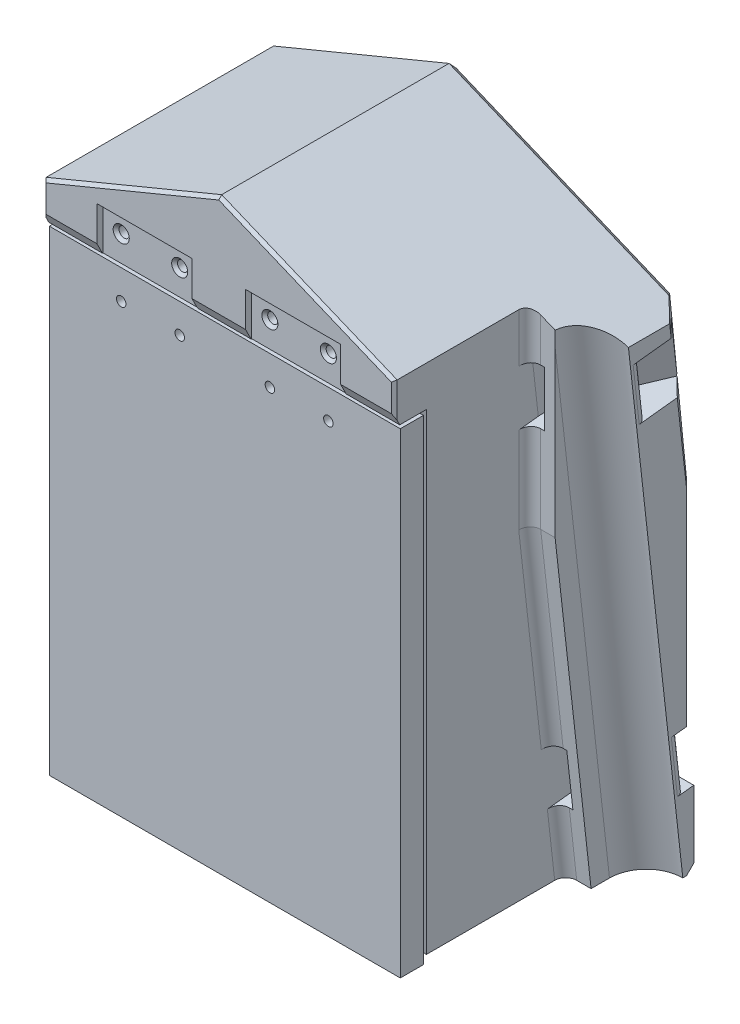
SolidWorks part; units mm, degrees
other "House"
other "Door"
other "Cover" parameters "D1"=134.3446, "D2"=7.568, "D3"=4.0473, "D4"=11.5
ref_plane "Front Plane" through (0, 0, 0) normal (0, 0, 1) x (1, 0, 0)
ref_plane "Top Plane" through (0, 0, 0) normal (0, 1, 0) x (1, 0, 0)
ref_plane "Right Plane" through (0, 0, 0) normal (1, 0, 0) x (0, 0, -1)
sketch "Sketch1" plane through (0, 0, 0) normal (0, 0, 1) x (1, 0, 0)
  line L0 (-48, 73.5589) -> (-48, -66.5589)
  line L1 (-45, -61.5589) -> (45, -61.5589)
  line L2 (-45, -61.5589) -> (-45, 61.5589)
  line L3 (-45, 61.5589) -> (45, 61.5589)
  line L4 (45, -61.5589) -> (45, 61.5589)
  line L5 (0, 61.5589) -> (0, -61.5589) construction
  line L6 (-45, 0) -> (45, 0) construction
  line L7 (-48, -66.5589) -> (48, -66.5589)
  line L8 (48, -66.5589) -> (48, 73.5589)
  line L9 (48, 73.5589) -> (0, 93.4411)
  line L10 (0, 93.4411) -> (-48, 73.5589)
  point P0 (0, 0)
  dimension "D1" = 160
  dimension "D2" = 90
  dimension "D3" = 22.5
  dimension "D4" = 12
  dimension "D5" = 5
  dimension "D6" = 3
  dimension "D7" = 123.1177
extrude "main-extrude" add sketch "Sketch1" along normal blind 60
sketch "Sketch2" plane through (0, 0, 0) normal (0, 0, 1) x (1, 0, 0)
  line L0 (48, -66.5589) -> (48, 73.5589) construction
  line L1 (-48, -66.5589) -> (48, -66.5589) construction
  line L2 (-48, 73.5589) -> (-48, -66.5589) construction
  line L3 (48, 73.5589) -> (0, 93.4411) construction
  line L4 (0, 93.4411) -> (-48, 73.5589) construction
  line L5 (48, -66.5589) -> (48, 73.5589)
  line L6 (-48, -66.5589) -> (48, -66.5589)
  line L7 (-48, 73.5589) -> (-48, -66.5589)
  line L8 (48, 73.5589) -> (0, 93.4411)
  line L9 (0, 93.4411) -> (-48, 73.5589)
extrude "rear-extrude" add sketch "Sketch2" against normal blind 5
sketch "Sketch6" plane through (0, -66.5589, 0) normal (0, -1, 0) x (1, 0, 0)
  line L0 (48, 22.9375) -> (53, 22.9375)
  line L1 (64.9375, 15) -> (64.9375, 22.9375)
  line L2 (53, 22.9375) -> (57, 22.9375)
  line L3 (-48, -5) -> (48, -5) construction
  line L4 (64.9375, 15) -> (64.9375, -5)
  line L5 (64.9375, -5) -> (48, -5)
  line L6 (48, 60) -> (48, -5) construction
  line L7 (48, -5) -> (48, 22.9375)
  line L8 (64.9375, 22.9375) -> (57, 22.9375)
  circle A0 centre (64.9375, 22.9375) radius 7.9375 construction
  arc A1 (64.9375, 15) -> (57, 22.9375) centre (64.9375, 22.9375) cw construction
  point P3 (64.9375, 15)
  dimension "D3" = 15.875
  dimension "D1" = 5
  dimension "D2" = 4
  dimension "D4" = 20
extrude "Boss-Extrude3" add sketch "Sketch6" against normal up to surface (140.1177 mm away)
sketch "Sketch19" plane through (64.9375, 0, 0) normal (1, 0, 0) x (0, 0, -1)
  line L0 (-7.4036, -72.4527) -> (-21.3291, 52.151) construction
  line L2 (-22.9375, 66.5431) -> (-32.8756, 65.4325) construction
  line L3 (-7.9381, -67.6695) -> (2, -66.5589) construction
  line L6 (5, -66.5589) -> (-22.9375, -66.5589) construction
  dimension "D1" = 10
  dimension "D3" = 3
ref_plane "Plane6" through (64.9375, -67.6695, 7.9381) normal (0, 0.9938, 0.1111) x (1, 0, 0)
sketch "Sketch20" plane through (64.9375, -67.6695, 7.9381) normal (0, 0.9938, 0.1111) x (1, 0, 0)
  line L0 (10, 0) -> (10, -24.5664)
  line L3 (10, -24.5664) -> (-16.9375, -24.5664)
  line L4 (21.2132, 0) -> (-21.2132, 42.4264)
  line L5 (-21.2132, 42.4264) -> (21.2132, 42.4264)
  line L6 (21.2132, 42.4264) -> (21.2132, 0)
  line L7 (0, 0) -> (10.6066, 10.6066) construction
  line L8 (-10, 0) -> (-10, -5)
  line L9 (-10, -5) -> (-16.9375, -5)
  line L10 (-16.9375, -5) -> (-16.9375, -24.5664)
  circle A0 centre (0, 0) radius 10 construction
  circle A3 centre (0, 0) radius 15 construction
  arc A4 (-10, 0) -> (10, 0) centre (0, 0) cw
  point P16 (10.6066, 10.6066)
  point P18 (10.6066, 10.6066)
  point P19 (10.6066, 10.6066)
  point P20 (10.6066, 10.6066)
  point P21 (10.6066, 10.6066)
  point P22 (7.0711, 7.0711)
  dimension "D1" = 20
  dimension "D2" = 5
  dimension "D3" = 5
extrude "Cut-Extrude9" cut sketch "Sketch20" along normal through all
ref_plane "Plane1" through (64.9375, -47.7933, 10.1595) normal (0, 0.9938, 0.1111) x (1, 0, 0)
ref_plane "Plane2" through (0, 0, 0) normal (0, 0.9938, 0.1111) x (1, 0, 0)
sketch "Sketch7" plane through (64.9375, -47.7933, 10.1595) normal (0, 0.9938, 0.1111) x (1, 0, 0)
  line L0 (-16.9375, -15) -> (-12.9375, -15)
  line L2 (-16.9375, -5) -> (-10, -5) construction
  line L4 (-12.9375, -15) -> (-12.9375, -5)
  line L5 (-12.9375, -5) -> (-12.9375, 0)
  line L6 (-16.9375, -15) -> (-16.9375, 0)
  line L7 (0, 12.9375) -> (49.3366, 12.9375)
  line L10 (-16.9375, -51.6164) -> (-16.9375, -5) construction
  line L11 (-14.6683, 8.4687) -> (10, 51.1955)
  line L12 (10, 0) -> (10, -24.5664) construction
  line L13 (49.3366, 12.9375) -> (10, 51.1955)
  arc A2 (-12.9375, 0) -> (0, 12.9375) centre (0, 0) cw
  arc A3 (-14.6683, 8.4687) -> (-16.9375, 0) centre (0, 0) ccw
  circle A5 centre (0, 0) radius 10 construction
  dimension "D1" = 4
  dimension "D2" = 60
  dimension "D3" = 10
extrude "Cut-Extrude10" cut sketch "Sketch7" along normal blind 15
pattern_linear "LPattern1" count 2 spacing 94 along (0, 0.9938, 0.1111) of "Cut-Extrude10"
fillet "Fillet2" radius 3 4 edges at (48, 67.0081, 22.9375) (48, 33.4445, 22.9375) (48, -57.4537, 14.111) (48, -5.9581, 19.866)
sketch "Sketch9" plane through (0, -66.5589, 0) normal (0, -1, 0) x (1, 0, 0)
  line L0 (-48, 0) -> (48, 0) construction
  line L3 (-30, 3) -> (0, 3) construction
  line L4 (0, 3) -> (30, 3) construction
  circle A0 centre (-30, 3) radius 3
  circle A1 centre (0, 3) radius 3
  circle A2 centre (30, 3) radius 3
  dimension "D1" = 6
  dimension "D2" = 30
extrude "inner-drain-holes" cut sketch "Sketch9" against normal blind 15
sketch "Sketch4" plane through (0, 0, 60) normal (0, 0, 1) x (1, 0, 0)
  line L0 (-48, 73.5589) -> (-48, -66.5589) construction
  line L1 (-48, 61.5589) -> (48, 61.5589) construction
  line L2 (-48, 61.5589) -> (-48, -66.5589)
  line L3 (-48, -66.5589) -> (48, -66.5589)
  line L4 (48, 61.5589) -> (48, -66.5589)
  line L5 (48, -66.5589) -> (48, 73.5589) construction
  line L6 (-48, 61.5589) -> (-48, 62.5589)
  line L7 (-48, 73.5589) -> (-48, -66.5589) construction
  line L8 (-48, 62.5589) -> (48, 62.5589)
  line L9 (48, -66.5589) -> (48, 73.5589) construction
  line L10 (48, 62.5589) -> (48, 61.5589)
  dimension "D1" = 1
extrude "Cut-Extrude2" cut sketch "Sketch4" against normal blind 8
sketch "Sketch5" plane through (0, 0, 60) normal (0, 0, 1) x (1, 0, 0)
  line L0 (-33.3333, 61.5589) -> (-7.3333, 61.5589) construction
  line L1 (-33.3333, 48.0589) -> (-7.3333, 48.0589)
  line L2 (-33.3333, 48.0589) -> (-33.3333, 75.0589)
  line L3 (-33.3333, 75.0589) -> (-7.3333, 75.0589)
  line L4 (-7.3333, 48.0589) -> (-7.3333, 75.0589)
  line L5 (-20.3333, 75.0589) -> (-20.3333, 48.0589) construction
  line L6 (-33.3333, 61.5589) -> (-7.3333, 61.5589) construction
  line L7 (-45, 61.5589) -> (45, 61.5589) construction
  line L8 (-48, 61.5589) -> (48, 61.5589) construction
  line L9 (0, -987.8214) -> (0, 49012.1786) construction
  line L10 (-33.3333, 61.5589) -> (-48, 61.5589) construction
  line L11 (-48, 73.5589) -> (-48, -66.5589) construction
  line L12 (33.3333, 75.0589) -> (7.3333, 75.0589)
  line L13 (7.3333, 48.0589) -> (7.3333, 75.0589)
  line L14 (33.3333, 48.0589) -> (7.3333, 48.0589)
  line L15 (33.3333, 48.0589) -> (33.3333, 75.0589)
  line L16 (-7.3333, 61.5589) -> (7.3333, 61.5589) construction
  point P0 (-20.3333, 61.5589)
  dimension "D1" = 27
  dimension "D2" = 26
extrude "Cut-Extrude3" cut sketch "Sketch5" against normal offset from surface (1.65 mm away) 6.35 up to face at (0, 0, 52)
sketch "Sketch15" plane through (0, 0, 58.35) normal (0, 0, 1) x (1, 0, 0)
  line L0 (-28.3333, 69.5589) -> (-12.3333, 69.5589) construction
  line L1 (0, -934.1648) -> (0, 49065.8352) construction
  line L2 (0, -200987.8214) -> (0, 249012.1786) construction
  line L3 (-20.3333, 75.0589) -> (-20.3333, 48.0589) construction
  line L4 (-33.3333, 61.5589) -> (-7.3333, 61.5589) construction
  circle A0 centre (-28.3333, 69.5589) radius 1.4
  circle A1 centre (-12.3333, 69.5589) radius 1.4
  circle A2 centre (28.3333, 69.5589) radius 1.4
  circle A3 centre (12.3333, 69.5589) radius 1.4
  point P8 (-20.3333, 69.5589)
  dimension "D1" = 2.8
  dimension "D2" = 16
  dimension "D3" = 8
extrude "Cut-Extrude7" cut sketch "Sketch15" against normal blind 40
sketch "Sketch12" plane through (0, 0, 52) normal (0, 0, 1) x (1, 0, 0)
  line L5 (0, 61.5589) -> (0, -61.5589) construction
  line L6 (-48.001, 61.5589) -> (48.001, 61.5589)
  line L7 (-48.001, 61.5589) -> (-48.001, -68.5589)
  line L8 (-48.001, -68.5589) -> (48.001, -68.5589)
  line L9 (48.001, 61.5589) -> (48.001, -68.5589)
  line L10 (0, -68.5589) -> (0, 61.5589) construction
  line L11 (-48.001, -3.5) -> (48.001, -3.5) construction
  line L12 (-48, -66.5589) -> (48, -66.5589) construction
  line L13 (-48, 73.5589) -> (-48, -66.5589) construction
  point P0 (0, -3.5)
  dimension "D1" = 2
  dimension "D2" = 0.001
extrude "Boss-Extrude5" add sketch "Sketch12" along normal blind 6.35 separate body
sketch "Sketch13" plane through (0, 0, 58.35) normal (0, 0, 1) x (1, 0, 0)
  line L0 (-1053.3426, 61.5589) -> (48946.6574, 61.5589) construction
  line L1 (-33.3333, 61.5589) -> (-48, 61.5589) construction
  line L4 (7.3333, 48.0589) -> (33.3333, 48.0589)
  line L5 (33.3333, 48.0589) -> (33.3333, 75.0589)
  line L6 (33.3333, 75.0589) -> (7.3333, 75.0589)
  line L7 (7.3333, 75.0589) -> (7.3333, 48.0589)
  line L8 (7.3333, 48.0589) -> (33.3333, 48.0589) construction
  line L9 (33.3333, 48.0589) -> (33.3333, 75.0589) construction
  line L10 (33.3333, 75.0589) -> (7.3333, 75.0589) construction
  line L11 (7.3333, 75.0589) -> (7.3333, 48.0589) construction
  line L12 (-33.3333, 48.0589) -> (-7.3333, 48.0589)
  line L13 (-33.3333, 75.0589) -> (-33.3333, 48.0589)
  line L14 (-7.3333, 75.0589) -> (-33.3333, 75.0589)
  line L15 (-7.3333, 48.0589) -> (-7.3333, 75.0589)
  line L16 (-33.3333, 48.0589) -> (-7.3333, 48.0589) construction
  line L17 (-33.3333, 75.0589) -> (-33.3333, 48.0589) construction
  line L18 (-7.3333, 75.0589) -> (-33.3333, 75.0589) construction
  line L19 (-7.3333, 48.0589) -> (-7.3333, 75.0589) construction
  circle A0 centre (28.3333, 69.5589) radius 1.4 construction
  circle A1 centre (12.3333, 69.5589) radius 1.4 construction
  circle A2 centre (-28.3333, 69.5589) radius 1.4 construction
  circle A3 centre (-12.3333, 69.5589) radius 1.4 construction
  circle A4 centre (28.3333, 69.5589) radius 1.4 construction
  circle A5 centre (12.3333, 69.5589) radius 1.4 construction
  circle A6 centre (-28.3333, 69.5589) radius 1.4 construction
  circle A7 centre (-12.3333, 69.5589) radius 1.4 construction
  circle A8 centre (28.3333, 53.5589) radius 1.4 construction
  circle A9 centre (12.3333, 53.5589) radius 1.4 construction
  circle A10 centre (-12.3333, 53.5589) radius 1.4 construction
  circle A11 centre (-28.3333, 53.5589) radius 1.4 construction
  circle A12 centre (-28.3333, 53.5589) radius 1.3
  circle A13 centre (-12.3333, 53.5589) radius 1.3
  circle A14 centre (12.3333, 53.5589) radius 1.3
  circle A15 centre (28.3333, 53.5589) radius 1.3
  dimension "D3" = 2.6
  dimension "D1" = 0
  dimension "D2" = 0
extrude "Cut-Extrude8" cut sketch "Sketch13" against normal through all
chamfer "Chamfer4" distance 3 distance2 1.5 3 edges at (0, 62.5589, 60) (-40.6667, 62.5589, 60) (40.6667, 62.5589, 60)
chamfer "Chamfer7" distance 0.8 angle 45 4 edges at (26.9333, 69.5589, 58.35) (10.9333, 69.5589, 58.35) (-10.9333, 69.5589, 58.35) (-26.9333, 69.5589, 58.35)
fillet "cavity-fillet" radius 5 4 edges at (45, -61.5589, 26) (-45, -61.5589, 26) (45, 61.5589, 26) (-45, 61.5589, 26)
sketch "Sketch21" plane through (0, 0, 0) normal (0, 0, 1) x (1, 0, 0)
  line L14 (30, -61.0589) -> (40, -61.0589)
  line L15 (44.5, -56.5589) -> (44.5, 56.5589)
  line L16 (40, 61.0589) -> (-40, 61.0589)
  line L17 (-44.5, 56.5589) -> (-44.5, -56.5589)
  line L18 (-40, -61.0589) -> (-30, -61.0589)
  line L19 (-30, -61.0589) -> (0, -61.0589)
  line L20 (0, -61.0589) -> (30, -61.0589)
  line L21 (30, -61.0589) -> (40, -61.0589)
  line L22 (44.5, -56.5589) -> (44.5, 56.5589)
  line L23 (40, 61.0589) -> (-40, 61.0589)
  line L24 (-44.5, 56.5589) -> (-44.5, -56.5589)
  line L25 (-40, -61.0589) -> (-30, -61.0589)
  line L26 (-30, -61.0589) -> (0, -61.0589)
  line L27 (0, -61.0589) -> (30, -61.0589)
  circle A4 centre (-38.5, 55.0589) radius 6 construction
  circle A5 centre (38.5, 55.0589) radius 6 construction
  circle A6 centre (38.5, -55.0589) radius 6 construction
  circle A7 centre (-38.5, -55.0589) radius 6 construction
  arc A8 (40, -61.0589) -> (44.5, -56.5589) centre (40, -56.5589) ccw
  arc A9 (44.5, 56.5589) -> (40, 61.0589) centre (40, 56.5589) ccw
  arc A10 (-40, 61.0589) -> (-44.5, 56.5589) centre (-40, 56.5589) ccw
  arc A11 (-44.5, -56.5589) -> (-40, -61.0589) centre (-40, -56.5589) ccw
  arc A12 (40, -61.0589) -> (44.5, -56.5589) centre (40, -56.5589) ccw
  arc A13 (44.5, 56.5589) -> (40, 61.0589) centre (40, 56.5589) ccw
  arc A14 (-40, 61.0589) -> (-44.5, 56.5589) centre (-40, 56.5589) ccw
  arc A15 (-44.5, -56.5589) -> (-40, -61.0589) centre (-40, -56.5589) ccw
  circle A17 centre (-38.5, 55.0589) radius 1.3
  circle A18 centre (38.5, 55.0589) radius 1.3
  circle A19 centre (-38.5, -55.0589) radius 1.3
  circle A20 centre (38.5, -55.0589) radius 1.3
  dimension "D2" = 12
  dimension "D5" = 2.6
  dimension "D1" = 0.5
  dimension "D3" = 2
  dimension "D4" = 2
extrude "Boss-Extrude10" add sketch "Sketch21" along normal blind 3 separate body
sketch "Sketch22" plane through (0, 0, 0) normal (0, 0, 1) x (1, 0, 0)
  circle A0 centre (-38.5, 55.0589) radius 2
  circle A1 centre (38.5, 55.0589) radius 2
  circle A2 centre (-38.5, -55.0589) radius 2
  circle A3 centre (38.5, -55.0589) radius 2
  circle A4 centre (-38.5, 55.0589) radius 1.3 construction
  circle A5 centre (38.5, 55.0589) radius 1.3 construction
  circle A6 centre (38.5, -55.0589) radius 1.3 construction
  circle A7 centre (-38.5, -55.0589) radius 1.3 construction
  dimension "D1" = 4
extrude "Cut-Extrude11" cut sketch "Sketch22" against normal through all
chamfer "Chamfer6" distance 0.8 angle 45 11 edges at (-45, 0, 52) (-43.5355, 60.0944, 52) (-43.5355, -60.0944, 52) (0, 61.5589, 52) (0, -61.5589, 52) (43.5355, 60.0944, 52) (43.5355, -60.0944, 52) (45, 0, 52) (-48, -2, 52) (48, -2, 52) (0, -66.5589, 52)
chamfer "Chamfer2" distance 2 angle 45 4 edges at (8.4687, -66.5589, -5) (-48, 3.5, -5) (-24, 83.5, -5) (29.0351, 81.4144, -5)
chamfer "Chamfer9" distance 0.8 angle 45 4 edges at (-48, 69.5589, 60) (48, 69.5589, 60) (24, 83.5, 60) (-24, 83.5, 60)
fillet "Fillet3" radius 2 2 edges at (64.9375, -38.9028, -1.865) (64.9375, 54.5157, 8.5753)
equation "\"D1@Sketch19\"=\"D4@Sketch6\"/2"
